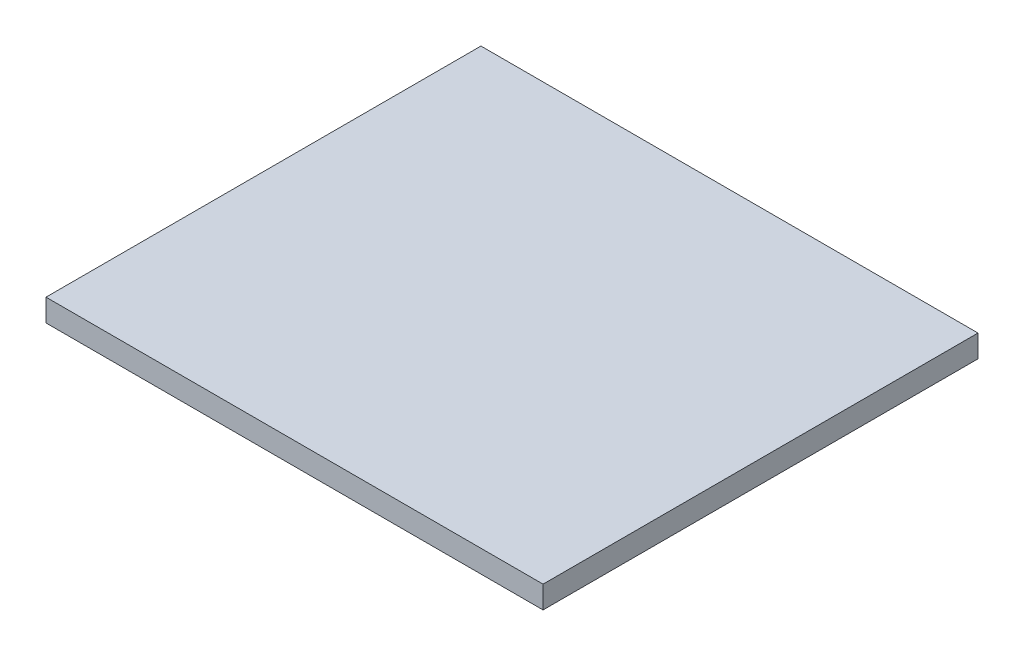
SolidWorks part; units mm, degrees
ref_plane "Front Plane" through (0, 0, 0) normal (0, 0, 1) x (1, 0, 0)
ref_plane "Top Plane" through (0, 0, 0) normal (0, 1, 0) x (1, 0, 0)
ref_plane "Right Plane" through (0, 0, 0) normal (1, 0, 0) x (0, 0, -1)
sketch "Esquisse1" plane through (0, 0, 0) normal (0, 1, 0) x (1, 0, 0)
  line L1 (-200, 175) -> (200, 175)
  line L2 (-200, 175) -> (-200, -175)
  line L3 (-200, -175) -> (200, -175)
  line L4 (200, 175) -> (200, -175)
  line L5 (-200, 175) -> (200, -175) construction
  line L6 (-200, -175) -> (200, 175) construction
  point P0 (0, 0)
extrude "Boss.-Extru.1" add sketch "Esquisse1" along normal blind 18
